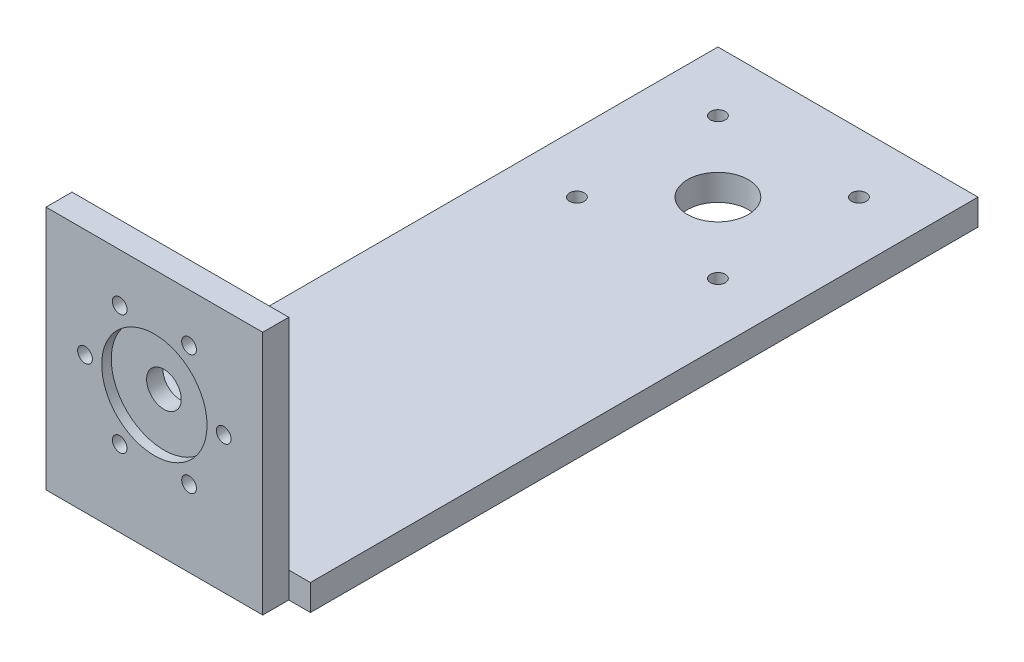
SolidWorks part; units mm, degrees
ref_plane "Front Plane" through (0, 0, 0) normal (0, 0, 1) x (1, 0, 0)
ref_plane "Top Plane" through (0, 0, 0) normal (0, 1, 0) x (1, 0, 0)
ref_plane "Right Plane" through (0, 0, 0) normal (1, 0, 0) x (0, 0, -1)
ref_plane "PL_Yaw_Plate_base" through (0, 0, -6) normal (0, 0, 1) x (1, 0, 0)
sketch "SK_Yaw_Plate" plane through (0, 0, -6) normal (0, 0, 1) x (1, 0, 0)
  line L0 (-25, -31.5) -> (25, -31.5)
  line L1 (25, -31.5) -> (25, 25)
  line L2 (25, 25) -> (-25, 25)
  line L3 (-25, 25) -> (-25, -31.5)
  circle A0 centre (16, 0) radius 1.7
  circle A1 centre (8, 13.8564) radius 1.7
  circle A2 centre (-8, 13.8564) radius 1.7
  circle A3 centre (-16, 0) radius 1.7
  circle A4 centre (-8, -13.8564) radius 1.7
  circle A5 centre (8, -13.8564) radius 1.7
  circle A6 centre (0, 0) radius 4
  dimension "D9_SK_Yaw_Plate" = 3.4
  dimension "D11_SK_Yaw_Plate" = 3.4
  dimension "D14_SK_Yaw_Plate" = 3.4
  dimension "D17_SK_Yaw_Plate" = 3.4
  dimension "D19_SK_Yaw_Plate" = 3.4
  dimension "D22_SK_Yaw_Plate" = 3.4
  dimension "D25_SK_Yaw_Plate" = 8
  dimension "P1" = 25
  dimension "P2" = 31.5
  dimension "P3" = 25
  dimension "P4" = 31.5
  dimension "P5" = 25
  dimension "P6" = 25
  dimension "P7" = 25
  dimension "P8" = 25
  dimension "P10" = 16
  dimension "P12" = 8
  dimension "P13" = 13.8564
  dimension "P15" = 8
  dimension "P16" = 13.8564
  dimension "P18" = 16
  dimension "P20" = 8
  dimension "P21" = 13.8564
  dimension "P23" = 8
  dimension "P24" = 13.8564
extrude "Yaw_Plate" add sketch "SK_Yaw_Plate" along normal blind 6
sketch "SK_Yaw_Pilot_Recess" plane through (0, 0, 0) normal (0, 0, 1) x (1, 0, 0)
  circle A0 centre (0, 0) radius 12.15
  dimension "D1_SK_Yaw_Pilot_Recess" = 24.3
extrude "Yaw_Pilot_Recess" cut sketch "SK_Yaw_Pilot_Recess" against normal blind 2.2
ref_plane "PL_Elbow_Plate_base" through (0, -31.5, 0) normal (0, 1, 0) x (1, 0, 0)
sketch "SK_Elbow_Plate" plane through (0, -31.5, 0) normal (0, 1, 0) x (1, 0, 0)
  line L0 (-30, 6) -> (30, 6)
  line L1 (30, 6) -> (30, 160)
  line L2 (30, 160) -> (-30, 160)
  line L3 (-30, 160) -> (-30, 6)
  circle A0 centre (16.2635, 146.2635) radius 1.7
  circle A1 centre (-16.2635, 146.2635) radius 1.7
  circle A2 centre (-16.2635, 113.7365) radius 1.7
  circle A3 centre (16.2635, 113.7365) radius 1.7
  circle A4 centre (0, 130) radius 7
  dimension "D9_SK_Elbow_Plate" = 3.4
  dimension "D12_SK_Elbow_Plate" = 3.4
  dimension "D15_SK_Elbow_Plate" = 3.4
  dimension "D18_SK_Elbow_Plate" = 3.4
  dimension "D21_SK_Elbow_Plate" = 14
  dimension "P1" = 30
  dimension "P2" = 6
  dimension "P3" = 30
  dimension "P4" = 6
  dimension "P5" = 30
  dimension "P6" = 160
  dimension "P7" = 30
  dimension "P8" = 160
  dimension "P10" = 16.2635
  dimension "P11" = 146.2635
  dimension "P13" = 16.2635
  dimension "P14" = 146.2635
  dimension "P16" = 16.2635
  dimension "P17" = 113.7365
  dimension "P19" = 16.2635
  dimension "P20" = 113.7365
  dimension "P22" = 130
extrude "Elbow_Plate" add sketch "SK_Elbow_Plate" along normal blind 6
equation "\"Elbow_z\" = -130"
